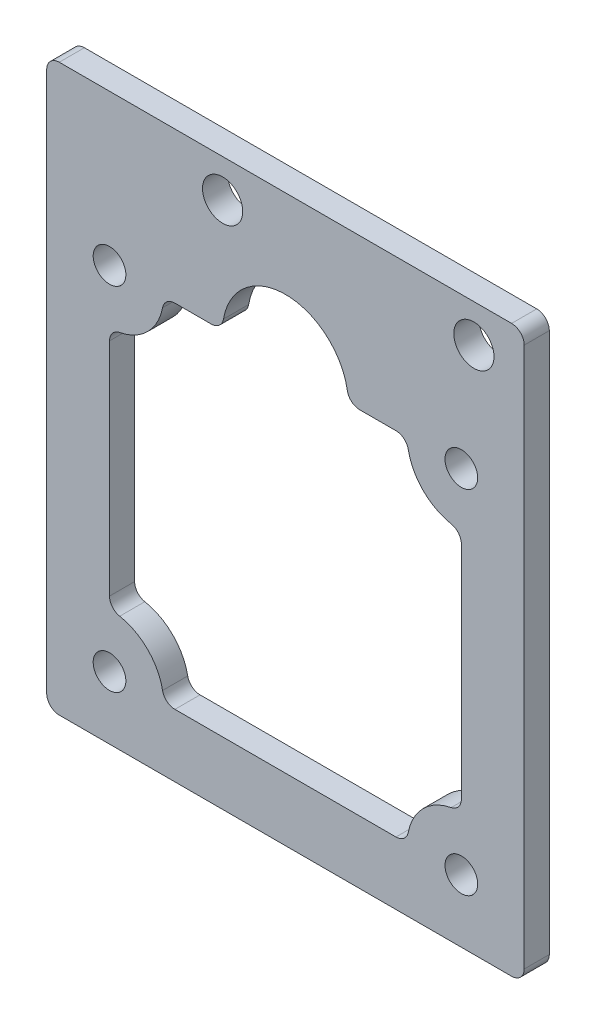
SolidWorks part; units mm, degrees
material "E-玻璃纤维"
ref_plane "前视基准面" through (0, 0, 0) normal (0, 0, 1) x (1, 0, 0)
ref_plane "上视基准面" through (0, 0, 0) normal (0, 1, 0) x (1, 0, 0)
ref_plane "右视基准面" through (0, 0, 0) normal (1, 0, 0) x (0, 0, -1)
sketch "草图1" plane through (0, 0, 0) normal (0, 0, 1) x (1, 0, 0)
  line L1 (-19, 19) -> (19, 19)
  line L2 (-19, 19) -> (-19, -19)
  line L3 (-19, -19) -> (19, -19)
  line L4 (19, 19) -> (19, -19)
  line L5 (-19, 19) -> (19, -19) construction
  line L6 (-19, -19) -> (19, 19) construction
  line L7 (-14, 14) -> (14, 14)
  line L8 (-14, 14) -> (-14, -14)
  line L9 (-14, -14) -> (14, -14)
  line L10 (14, 14) -> (14, -14)
  line L11 (-14, 14) -> (14, -14) construction
  line L12 (-14, -14) -> (14, 14) construction
  circle A0 centre (14, 14) radius 1.3
  circle A1 centre (-14, 14) radius 1.3
  circle A2 centre (-14, -14) radius 1.3
  circle A3 centre (14, -14) radius 1.3
  circle A4 centre (-14, 14) radius 4.3
  circle A5 centre (14, 14) radius 4.3
  circle A6 centre (14, -14) radius 4.3
  circle A7 centre (-14, -14) radius 4.3
  point P0 (0, 0)
  point P6 (0, 0)
  dimension "D3" = 2.6
  dimension "D1" = 28
  dimension "D2" = 38
  dimension "D4" = 3
extrude "凸台-拉伸1" add sketch "草图1" along normal blind 2 contours L4 L1 L2 L3 A7 L8 A4 L7 A5 L10 A6 L9 | L8 A4 L7 A1 | L7 A4 L8 A1 | L10 A5 L7 A0 | L7 A5 L10 A0 | L9 A6 L10 A3 | L10 A6 L9 A3 | L8 A7 L9 A2 | L9 A7 L8 A2
sketch "草图2" plane through (0, 0, 2) normal (0, 0, 1) x (1, 0, 0)
  line L0 (19, 19) -> (19, -19) construction
  line L1 (-19, 19) -> (19, 19)
  line L2 (-19, 19) -> (-19, 26)
  line L3 (-19, 26) -> (19, 26)
  line L4 (19, 19) -> (19, 26)
  line L5 (-5, 23) -> (15, 23) construction
  circle A0 centre (-5, 23) radius 1.6
  circle A1 centre (15, 23) radius 1.6
  dimension "D5" = 3.2
  dimension "D1" = 7
  dimension "D2" = 5
  dimension "D3" = 20
  dimension "D4" = 3
extrude "凸台-拉伸2" add sketch "草图2" against normal up to surface (2 mm away) up to face at (-12.7, -14, 0)
sketch "草图3" plane through (0, 0, 2) normal (0, 0, 1) x (1, 0, 0)
  line L0 (-9.7, 14) -> (9.7, 14) construction
  circle A0 centre (0, 14) radius 5
  dimension "D1" = 10
extrude "切除-拉伸1" cut sketch "草图3" against normal through all
fillet "圆角1" radius 1 14 edges at (19, 26, 1) (-19, -19, 1) (19, -19, 1) (9.7, 14, 1) (14, 9.7, 1) (14, -9.7, 1) (9.7, -14, 1) (-9.7, -14, 1) (-14, -9.7, 1) (-14, 9.7, 1) (-9.7, 14, 1) (5, 14, 1) (-5, 14, 1) (-19, 26, 1)
